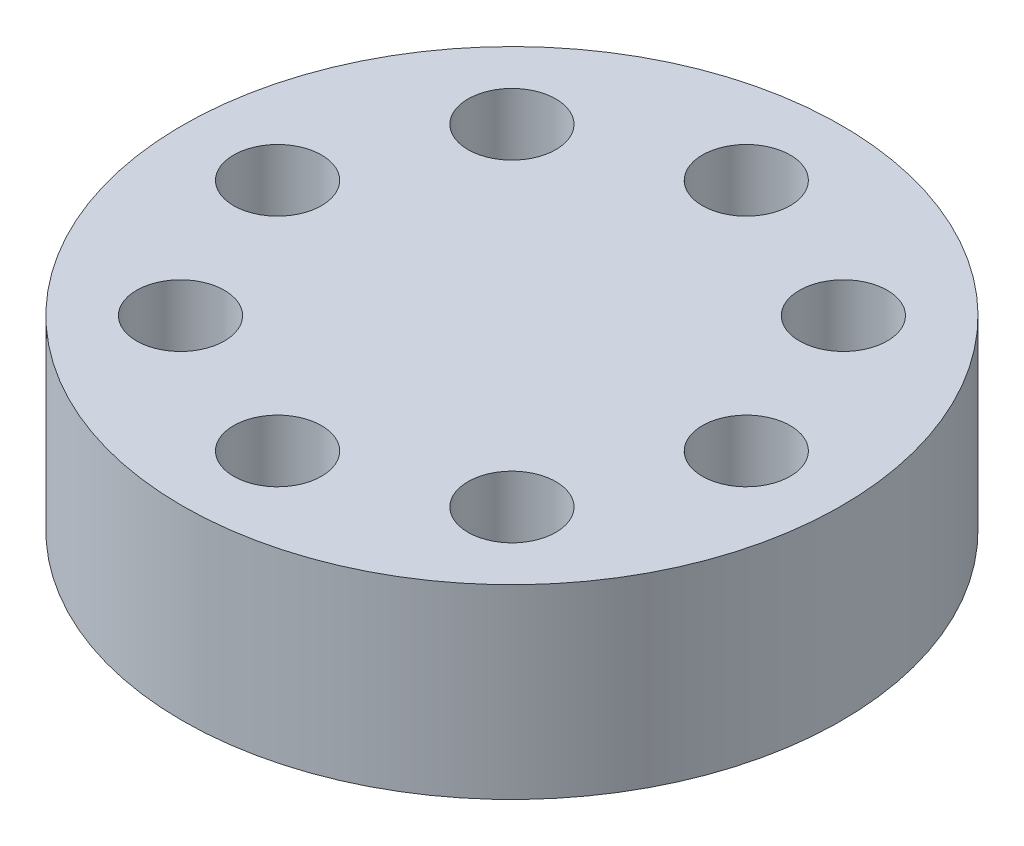
SolidWorks part; units mm, degrees
ref_plane "Front Plane" through (0, 0, 0) normal (0, 0, 1) x (1, 0, 0)
ref_plane "Top Plane" through (0, 0, 0) normal (0, 1, 0) x (1, 0, 0)
ref_plane "Right Plane" through (0, 0, 0) normal (1, 0, 0) x (0, 0, -1)
sketch "Sketch1" plane through (0, 0, 0) normal (0, 1, 0) x (1, 0, 0)
  circle A0 centre (0, 0) radius 22.5
  dimension "D1" = 45
extrude "Boss-Extrude1" add sketch "Sketch1" along normal blind 12.7
sketch "Sketch2" plane through (0, 12.7, 0) normal (0, 1, 0) x (1, 0, 0)
  circle A0 centre (0, 0) radius 16 construction
  circle A1 centre (-16, 0) radius 3
  circle A2 centre (-11.3137, 11.3137) radius 3
  circle A3 centre (0, 16) radius 3
  circle A4 centre (11.3137, 11.3137) radius 3
  circle A5 centre (16, 0) radius 3
  circle A6 centre (11.3137, -11.3137) radius 3
  circle A7 centre (0, -16) radius 3
  circle A8 centre (-11.3137, -11.3137) radius 3
  point P21 (0, 0)
  dimension "D1" = 32
  dimension "D2" = 6
  dimension "D3" = 8
extrude "Cut-Extrude1" cut sketch "Sketch2" against normal through all
equation "\"L1L\"=500"
equation "\"L1Thick\"=6.35"
equation "\"Harm-Drive-Outer\"=74.5"
equation "\"L1-Spacing\"=115.65"
equation "\"L-Bracket-HoleToWall\"=12.5"
equation "\"L-Bracket-HoleToSide\"=11"
equation "\"Bracket-Hole-D\"=6.8"
equation "\"D1@Boss-Extrude1\"=\"L1Thick\"*2"
